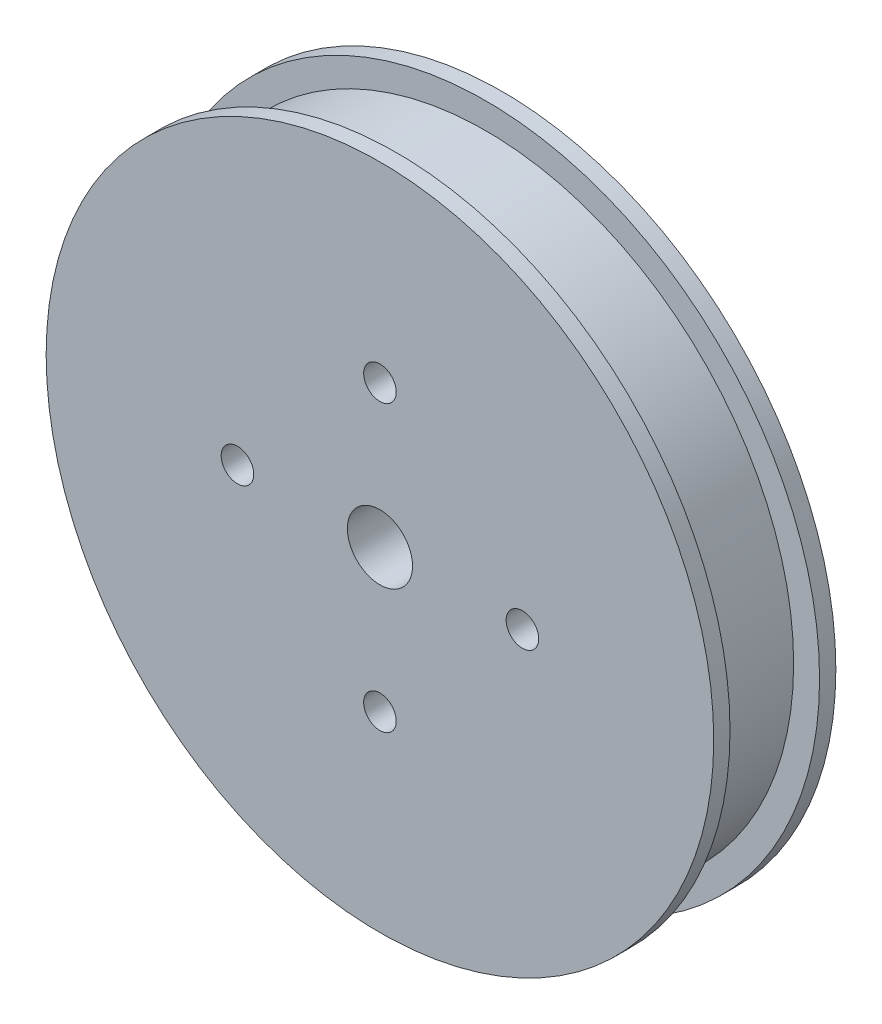
SolidWorks part; units mm, degrees
material "6061 Alloy"
ref_plane "Front" through (0, 0, 0) normal (0, 0, 1) x (1, 0, 0)
ref_plane "Top" through (0, 0, 0) normal (0, 1, 0) x (1, 0, 0)
ref_plane "Right" through (0, 0, 0) normal (1, 0, 0) x (0, 0, -1)
sketch "草图1" plane through (0, 0, 0) normal (0, 0, 1) x (1, 0, 0)
  circle A0 centre (0, 0) radius 41
  circle A1 centre (0, 0) radius 4
  circle A2 centre (0, 0) radius 17.5 construction
  circle A3 centre (-17.5, 0) radius 2
  circle A4 centre (0, 17.5) radius 2
  circle A5 centre (17.5, 0) radius 2
  circle A6 centre (0, -17.5) radius 2
  point P16 (0, 0)
  dimension "D1" = 82
  dimension "D2" = 8
  dimension "D3" = 35
  dimension "D4" = 4
  dimension "D5" = 4
extrude "凸台-拉伸1" add sketch "草图1" along normal blind 15
sketch "草图3" plane through (0, 0, 15) normal (0, 0, 1) x (1, 0, 0)
  circle A0 centre (0, 0) radius 37.815
  circle A1 centre (0, 0) radius 41
  dimension "D1" = 75.63
extrude "切除-拉伸1" cut sketch "草图3" against normal blind 11 from offset 2
